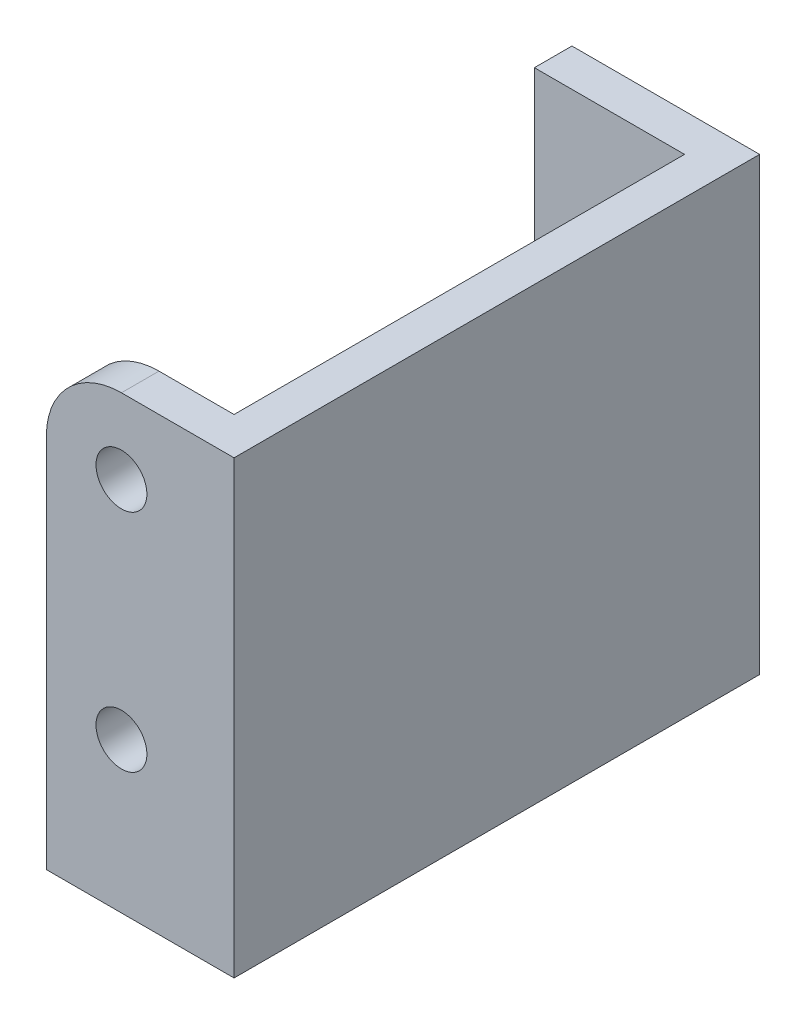
SolidWorks part; units mm, degrees
material "PET"
ref_plane "Front Plane" through (0, 0, 0) normal (0, 0, 1) x (1, 0, 0)
ref_plane "Top Plane" through (0, 0, 0) normal (0, 1, 0) x (1, 0, 0)
ref_plane "Right Plane" through (0, 0, 0) normal (1, 0, 0) x (0, 0, -1)
sketch "Sketch1" plane through (0, 0, 0) normal (0, 0, 1) x (1, 0, 0)
  line L1 (-7.9375, 19.05) -> (7.9375, 19.05)
  line L2 (-7.9375, 19.05) -> (-7.9375, -19.05)
  line L3 (-7.9375, -19.05) -> (7.9375, -19.05)
  line L4 (7.9375, 19.05) -> (7.9375, -19.05)
  line L5 (-7.9375, 19.05) -> (7.9375, -19.05) construction
  line L6 (-7.9375, -19.05) -> (7.9375, 19.05) construction
  point P0 (0, 0)
  dimension "D1" = 38.1
  dimension "D2" = 15.875
extrude "Boss-Extrude1" add sketch "Sketch1" against normal blind 44.45
shell "Shell1" thickness 3.175
sketch "Sketch2" plane through (0, 0, 0) normal (0, 0, 1) x (1, 0, 0)
  line L0 (7.9375, 19.05) -> (-7.9375, 19.05) construction
  line L1 (-7.9375, 19.05) -> (-7.9375, -19.05) construction
  circle A0 centre (-1.5875, -6.35) radius 2.1526
  circle A1 centre (-1.5875, 12.7) radius 2.1526
  point P8 (0, 0)
  dimension "D1" = 4.3053
  dimension "D2" = 19.05
  dimension "D3" = 6.35
  dimension "D4" = 6.35
extrude "Cut-Extrude1" cut sketch "Sketch2" against normal up to next
fillet "Fillet2" radius 6.35 1 edges at (-7.9375, 19.05, -1.5875)
